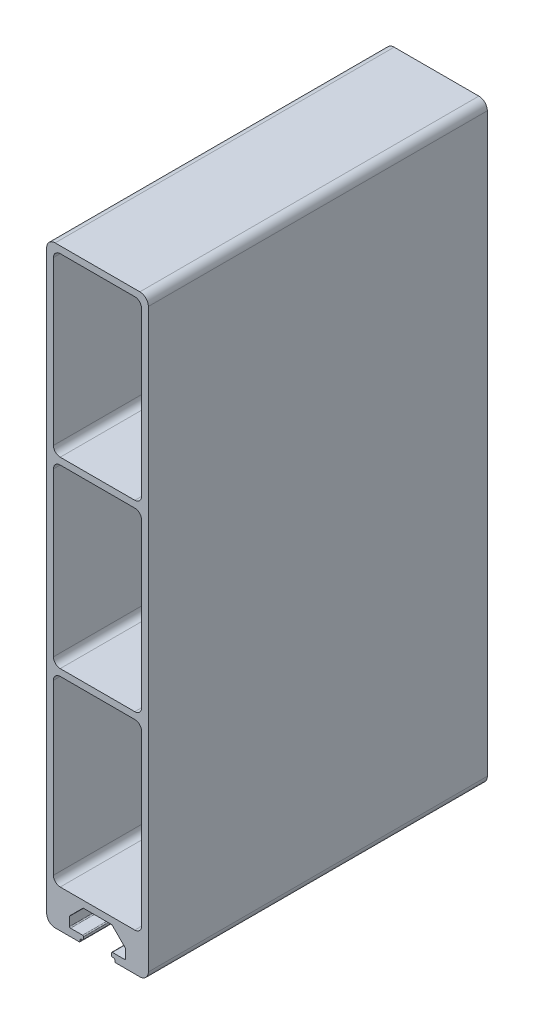
SolidWorks part; units mm, degrees
ref_plane "前视基准面" through (0, 0, 0) normal (0, 0, 1) x (1, 0, 0)
ref_plane "上视基准面" through (0, 0, 0) normal (0, 1, 0) x (1, 0, 0)
ref_plane "右视基准面" through (0, 0, 0) normal (1, 0, 0) x (0, 0, -1)
sketch "草图1" plane through (0, 0, 0) normal (0, 0, 1) x (1, 0, 0)
  line B0 (12.5, 0) -> (-12.5, 0)
  line B1 (11, -2) -> (-11, -2)
  line B2 (-15, -2.5) -> (-15, -172.5)
  line B3 (-13, -4) -> (-13, -52)
  line B4 (15, -2.5) -> (15, -172.5)
  line B5 (13, -4) -> (13, -52)
  line B6 (-5.4, -175) -> (-12.5, -175)
  line B7 (5.4, -175) -> (12.5, -175)
  line B8 (-5.1, -174.3) -> (-5.1, -174.7)
  line B9 (5.1, -174.3) -> (5.1, -174.7)
  line B10 (-4.8, -174) -> (-4.4, -174)
  line B11 (4.8, -174) -> (4.4, -174)
  line B12 (-4.1, -173.1) -> (-4.1, -173.7)
  line B13 (4.1, -173.1) -> (4.1, -173.7)
  line B14 (-7.95, -172.8) -> (-4.4, -172.8)
  line B15 (7.95, -172.8) -> (4.4, -172.8)
  line B16 (-8.25, -169.9299) -> (-8.25, -172.5)
  line B17 (8.25, -169.9299) -> (8.25, -172.5)
  line B18 (-4.3322, -165.8879) -> (-8.1621, -169.7178)
  line B19 (8.1621, -169.7178) -> (4.3322, -165.8879)
  line B20 (-4.1201, -165.8) -> (4.1201, -165.8)
  line B21 (11, -163.8) -> (-11, -163.8)
  line B22 (-11, -54) -> (11, -54)
  line B23 (-11, -56) -> (11, -56)
  line B24 (-11, -108) -> (11, -108)
  line B25 (13, -58) -> (13, -106)
  line B26 (-13, -58) -> (-13, -106)
  line B27 (-11, -110) -> (11, -110)
  line B28 (13, -112) -> (13, -161.8)
  line B29 (-13, -161.8) -> (-13, -112)
  arc B30 (-11, -2) -> (-13, -4) centre (-11, -4) ccw
  arc B31 (-12.5, 0) -> (-15, -2.5) centre (-12.5, -2.5) ccw
  arc B32 (15, -2.5) -> (12.5, 0) centre (12.5, -2.5) ccw
  arc B33 (11, -54) -> (13, -52) centre (11, -52) ccw
  arc B34 (13, -4) -> (11, -2) centre (11, -4) ccw
  arc B35 (-15, -172.5) -> (-12.5, -175) centre (-12.5, -172.5) ccw
  arc B36 (12.5, -175) -> (15, -172.5) centre (12.5, -172.5) ccw
  arc B37 (-5.4, -175) -> (-5.1, -174.7) centre (-5.4, -174.7) ccw
  arc B38 (5.1, -174.7) -> (5.4, -175) centre (5.4, -174.7) ccw
  arc B39 (-4.8, -174) -> (-5.1, -174.3) centre (-4.8, -174.3) ccw
  arc B40 (5.1, -174.3) -> (4.8, -174) centre (4.8, -174.3) ccw
  arc B41 (-4.4, -174) -> (-4.1, -173.7) centre (-4.4, -173.7) ccw
  arc B42 (4.1, -173.7) -> (4.4, -174) centre (4.4, -173.7) ccw
  arc B43 (-4.1, -173.1) -> (-4.4, -172.8) centre (-4.4, -173.1) ccw
  arc B44 (4.4, -172.8) -> (4.1, -173.1) centre (4.4, -173.1) ccw
  arc B45 (-8.25, -172.5) -> (-7.95, -172.8) centre (-7.95, -172.5) ccw
  arc B46 (7.95, -172.8) -> (8.25, -172.5) centre (7.95, -172.5) ccw
  arc B47 (-8.1621, -169.7178) -> (-8.25, -169.9299) centre (-7.95, -169.9299) ccw
  arc B48 (8.25, -169.9299) -> (8.1621, -169.7178) centre (7.95, -169.9299) ccw
  arc B49 (-4.1201, -165.8) -> (-4.3322, -165.8879) centre (-4.1201, -166.1) ccw
  arc B50 (4.3322, -165.8879) -> (4.1201, -165.8) centre (4.1201, -166.1) ccw
  arc B51 (-13, -52) -> (-11, -54) centre (-11, -52) ccw
  arc B52 (11, -108) -> (13, -106) centre (11, -106) ccw
  arc B53 (13, -58) -> (11, -56) centre (11, -58) ccw
  arc B54 (-13, -106) -> (-11, -108) centre (-11, -106) ccw
  arc B55 (-11, -56) -> (-13, -58) centre (-11, -58) ccw
  arc B56 (11, -163.8) -> (13, -161.8) centre (11, -161.8) ccw
  arc B57 (13, -112) -> (11, -110) centre (11, -112) ccw
  arc B58 (-13, -161.8) -> (-11, -163.8) centre (-11, -161.8) ccw
  arc B59 (-11, -110) -> (-13, -112) centre (-11, -112) ccw
sketch_block_instance "A$C56727E1D-1"
sketch_block "A$C56727E1D"
extrude "凸台-拉伸1" add sketch "草图1" along normal mid plane 100
